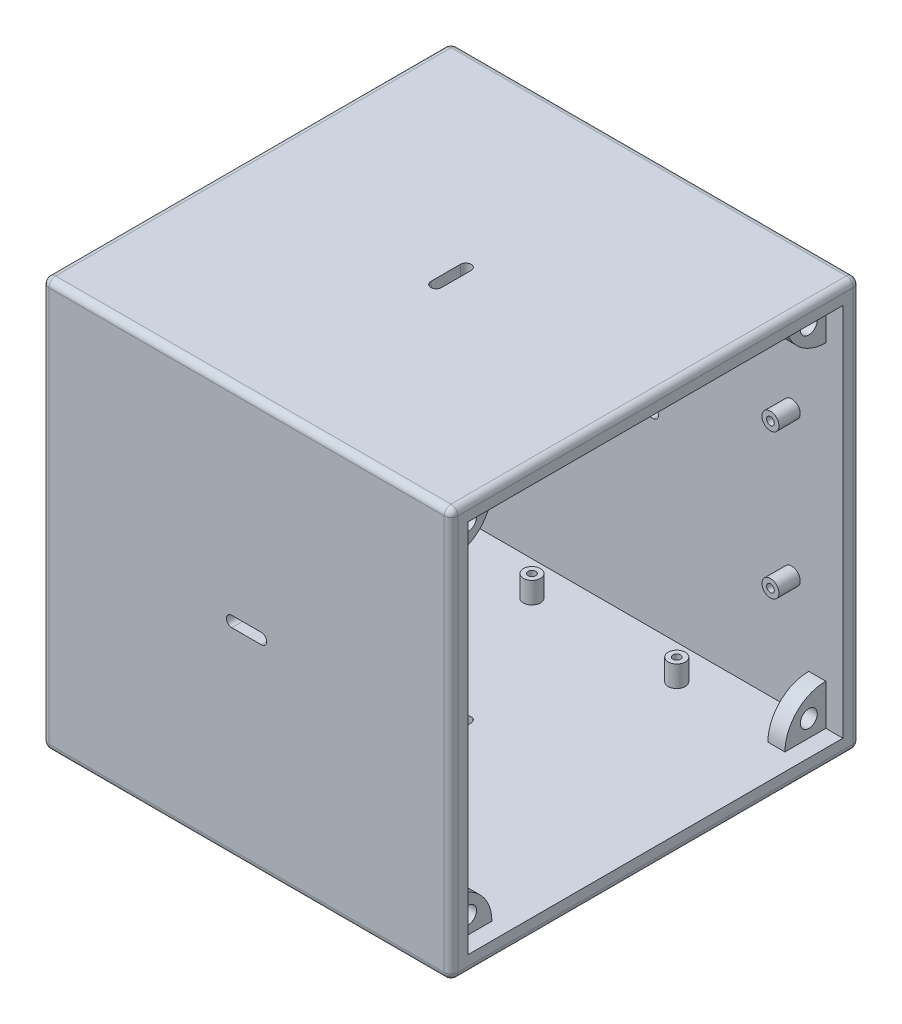
SolidWorks part; units mm, degrees
ref_plane "Front Plane" through (0, 0, 0) normal (0, 0, 1) x (1, 0, 0)
ref_plane "Top Plane" through (0, 0, 0) normal (0, 1, 0) x (1, 0, 0)
ref_plane "Right Plane" through (0, 0, 0) normal (1, 0, 0) x (0, 0, -1)
sketch "Sketch1" plane through (0, 0, 0) normal (0, 1, 0) x (1, 0, 0)
  line L1 (-76.2, -76.2) -> (76.2, -76.2)
  line L2 (-76.2, -76.2) -> (-76.2, 76.2)
  line L3 (-76.2, 76.2) -> (76.2, 76.2)
  line L4 (76.2, -76.2) -> (76.2, 76.2)
  line L5 (-76.2, -76.2) -> (76.2, 76.2) construction
  line L6 (-76.2, 76.2) -> (76.2, -76.2) construction
  point P0 (0, 0)
  dimension "D1" = 152.4
  dimension "D2" = 152.4
extrude "Boss-Extrude1" add sketch "Sketch1" along normal blind 152.4
shell "Shell2" thickness 6.35
ref_plane "Symmetry Top Plane" through (0, 76.2, 0) normal (0, 1, 0) x (1, 0, 0)
sketch "Sketch2" plane through (-69.85, 0, 0) normal (1, 0, 0) x (0, 0, -1)
  line L0 (-5.5, 76.2) -> (5.5, 76.2) construction
  line L1 (-7.5, 74.2) -> (7.5, 74.2) construction
  line L2 (-7.5, 74.2) -> (-7.5, 78.2) construction
  line L3 (-7.5, 78.2) -> (7.5, 78.2) construction
  line L4 (7.5, 74.2) -> (7.5, 78.2) construction
  line L5 (-7.5, 74.2) -> (7.5, 78.2)
  line L6 (-7.5, 78.2) -> (7.5, 74.2)
  line L7 (-5.5, 78.2) -> (5.5, 78.2)
  line L8 (-5.5, 74.2) -> (5.5, 74.2)
  line L10 (19, 73.2) -> (31, 73.2)
  line L11 (19, 73.2) -> (19, 79.2)
  line L12 (19, 79.2) -> (31, 79.2)
  line L13 (31, 73.2) -> (31, 79.2)
  line L14 (19, 73.2) -> (31, 79.2) construction
  line L15 (19, 79.2) -> (31, 73.2) construction
  line L16 (-31, 73.2) -> (-19, 73.2)
  line L17 (-31, 73.2) -> (-31, 79.2)
  line L18 (-31, 79.2) -> (-19, 79.2)
  line L19 (-19, 73.2) -> (-19, 79.2)
  line L20 (-31, 73.2) -> (-19, 79.2) construction
  line L21 (-31, 79.2) -> (-19, 73.2) construction
  arc A0 (-5.5, 78.2) -> (-5.5, 74.2) centre (-5.5, 76.2) ccw
  arc A1 (5.5, 74.2) -> (5.5, 78.2) centre (5.5, 76.2) ccw
  point P0 (0, 76.2)
  point P8 (0, 76.2)
  point P13 (-7.5, 76.2)
  point P14 (7.5, 76.2)
  point P15 (25, 76.2)
  point P20 (-25, 76.2)
  dimension "D6" = 2
  dimension "D1" = 15
  dimension "D2" = 4
  dimension "D3" = 76.2
  dimension "D4" = 0
  dimension "D5" = 25
  dimension "D7" = 15
  dimension "D8" = 12
  dimension "D9" = 6
  dimension "D10" = 25
  dimension "D11" = 25
  dimension "D12" = 6
  dimension "D13" = 12
  dimension "D14" = 25
extrude "Cut-Extrude3" cut sketch "Sketch2" along direction (1, 0, 0) on the side against the normal blind 6.35 contours L8 A1 L6 L5 A0 | L6 A1 L5 | L5 A1 L7 A0 L6 | L6 A0 L5
sketch "Sketch3" plane through (0, 0, -69.85) normal (0, 0, 1) x (1, 0, 0)
  line L0 (-5.5, 76.2) -> (5.5, 76.2) construction
  line L1 (-7.5, 74.2) -> (7.5, 74.2) construction
  line L2 (-7.5, 74.2) -> (-7.5, 78.2) construction
  line L3 (-7.5, 78.2) -> (7.5, 78.2) construction
  line L4 (7.5, 74.2) -> (7.5, 78.2) construction
  line L5 (-7.5, 74.2) -> (7.5, 78.2)
  line L6 (-7.5, 78.2) -> (7.5, 74.2)
  line L7 (-5.5, 78.2) -> (5.5, 78.2)
  line L8 (-5.5, 74.2) -> (5.5, 74.2)
  arc A0 (-5.5, 78.2) -> (-5.5, 74.2) centre (-5.5, 76.2) ccw
  arc A1 (5.5, 74.2) -> (5.5, 78.2) centre (5.5, 76.2) ccw
  point P0 (0, 76.2)
  point P7 (0, 76.2)
  point P12 (-7.5, 76.2)
  point P13 (7.5, 76.2)
  dimension "D3" = 2
  dimension "D6" = 76.2
  dimension "D1" = 15
  dimension "D2" = 4
  dimension "D4" = 15
  dimension "D5" = 0
extrude "Cut-Extrude4" cut sketch "Sketch3" against normal blind 6.35 contours L8 A1 L7 A0
sketch "Sketch4" plane through (0, 0, 69.85) normal (0, 0, -1) x (-1, 0, 0)
  line L0 (-5.5, 76.2) -> (5.5, 76.2) construction
  line L1 (-7.5, 74.2) -> (7.5, 74.2) construction
  line L2 (-7.5, 74.2) -> (-7.5, 78.2) construction
  line L3 (-7.5, 78.2) -> (7.5, 78.2) construction
  line L4 (7.5, 74.2) -> (7.5, 78.2) construction
  line L5 (-7.5, 74.2) -> (7.5, 78.2)
  line L6 (-7.5, 78.2) -> (7.5, 74.2)
  line L7 (-5.5, 78.2) -> (5.5, 78.2)
  line L8 (-5.5, 74.2) -> (5.5, 74.2)
  arc A0 (-5.5, 78.2) -> (-5.5, 74.2) centre (-5.5, 76.2) ccw
  arc A1 (5.5, 74.2) -> (5.5, 78.2) centre (5.5, 76.2) ccw
  point P0 (0, 76.2)
  point P7 (0, 76.2)
  point P12 (-7.5, 76.2)
  point P13 (7.5, 76.2)
  dimension "D3" = 2
  dimension "D1" = 15
  dimension "D2" = 4
  dimension "D4" = 15
  dimension "D5" = 0
  dimension "D6" = 76.2
extrude "Cut-Extrude5" cut sketch "Sketch4" against normal blind 6.35 contours L7 A1 L8 A0
sketch "Sketch5" plane through (0, 146.05, 0) normal (0, -1, 0) x (1, 0, 0)
  line L0 (0, -5.5) -> (0, 5.5) construction
  line L1 (-2, -5.5) -> (-2, 5.5)
  line L2 (2, -5.5) -> (2, 5.5)
  arc A0 (-2, -5.5) -> (2, -5.5) centre (0, -5.5) ccw
  arc A1 (2, 5.5) -> (-2, 5.5) centre (0, 5.5) ccw
  point P2 (0, 0)
  point P8 (0, -7.5)
  point P9 (0, 7.5)
  dimension "D1" = 15
  dimension "D2" = 4
extrude "Cut-Extrude6" cut sketch "Sketch5" against normal blind 6.35
mirror "Mirror1" about plane through (0, 76.2, 0) normal (0, 1, 0) of "Cut-Extrude6"
sketch "Sketch6" plane through (0, 146.05, 0) normal (0, -1, 0) x (1, 0, 0)
  line L0 (76.2, -76.2) -> (69.85, -76.2) construction
  line L1 (76.2, -76.2) -> (-76.2, -76.2) construction
  line L3 (69.85, -76.2) -> (63.5, -76.2)
  line L4 (69.85, -76.2) -> (69.85, 76.2)
  line L5 (69.85, 76.2) -> (63.5, 76.2)
  line L6 (63.5, -76.2) -> (63.5, 76.2)
  dimension "D1" = 6.35
  dimension "D2" = 152.4
  dimension "D3" = 6.35
extrude "Boss-Extrude2" add sketch "Sketch6" along normal blind 139.7
sketch "Sketch7" plane through (69.85, 0, 0) normal (1, 0, 0) x (0, 0, -1)
  line L0 (-69.85, 146.05) -> (69.85, 146.05) construction
  line L1 (69.85, 146.05) -> (69.85, 6.35) construction
  line L2 (-69.85, 6.35) -> (-69.85, 146.05) construction
  line L3 (69.85, 146.05) -> (69.85, 6.35) construction
  line L4 (69.85, 6.35) -> (-69.85, 6.35) construction
  line L5 (69.85, 21.59) -> (69.85, 130.81)
  line L6 (54.61, 146.05) -> (-54.61, 146.05)
  line L7 (-69.85, 21.59) -> (-69.85, 130.81)
  line L8 (54.61, 6.35) -> (-54.61, 6.35)
  arc A0 (54.61, 146.05) -> (69.85, 130.81) centre (69.85, 146.05) ccw
  arc A1 (-54.61, 146.05) -> (-69.85, 130.81) centre (-69.85, 146.05) cw
  arc A2 (69.85, 21.59) -> (54.61, 6.35) centre (69.85, 6.35) ccw
  arc A3 (-69.85, 21.59) -> (-54.61, 6.35) centre (-69.85, 6.35) cw
  dimension "D1" = 15.24
  dimension "D2" = 15.24
  dimension "D3" = 15.24
  dimension "D4" = 15.24
extrude "Cut-Extrude7" cut sketch "Sketch7" against normal blind 6.35
sketch "Sketch8" plane through (69.85, 0, 0) normal (1, 0, 0) x (0, 0, -1)
  line L1 (76.835, 76.2) -> (-76.835, 76.2) construction
  line L2 (0, 83.82) -> (0, -83.82) construction
  circle A0 centre (63.5, 12.7) radius 3.175
  circle A1 centre (63.5, 139.7) radius 3.175
  circle A2 centre (-63.5, 139.7) radius 3.175
  circle A3 centre (-63.5, 12.7) radius 3.175
  point P5 (63.4563, 12.9858)
  dimension "D1" = 6.35
  dimension "D2" = 6.35
  dimension "D3" = 6.35
extrude "Cut-Extrude8" cut sketch "Sketch8" against normal blind 6.35
sketch "Sketch10" plane through (0, 0, 69.85) normal (0, 0, -1) x (-1, 0, 0)
  circle A1 centre (-57.15, 49.2125) radius 1.4288
  circle A2 centre (57.15, 49.2125) radius 1.4288
  circle A3 centre (-57.15, 103.1875) radius 1.4288
  circle A6 centre (57.15, 103.1875) radius 1.4287
  circle A7 centre (-57.15, 103.1875) radius 3.175
  circle A8 centre (-57.15, 49.2125) radius 3.175
  circle A9 centre (57.15, 49.2125) radius 3.175
  circle A10 centre (57.15, 103.1875) radius 3.175
  dimension "D1" = 114.3
  dimension "D3" = 2.8575
  dimension "D4" = 2.8575
  dimension "D5" = 2.8575
  dimension "D6" = 2.8575
  dimension "D13" = 6.35
  dimension "D14" = 6.35
  dimension "D15" = 6.35
  dimension "D16" = 6.35
  dimension "D2" = 53.975
  dimension "D7" = 114.3
  dimension "D8" = 53.975
  dimension "D9" = 57.15
  dimension "D10" = 49.2125
  dimension "D11" = 57.15
  dimension "D12" = 57.15
extrude "Boss-Extrude3" add sketch "Sketch10" along normal blind 7.9375
mirror "Mirror2" about plane through (0, 0, 0) normal (0, 0, 1) of "Boss-Extrude3"
sketch "Sketch11" plane through (0, 6.35, 0) normal (0, 1, 0) x (1, 0, 0)
  circle A0 centre (26.9875, -57.15) radius 1.4288
  circle A1 centre (26.9875, 57.15) radius 1.4288
  circle A2 centre (-26.9875, -57.15) radius 1.4288
  circle A3 centre (-26.9875, 57.15) radius 1.4287
  circle A4 centre (-26.9875, -57.15) radius 3.175
  circle A5 centre (26.9875, -57.15) radius 3.175
  circle A6 centre (26.9875, 57.15) radius 3.175
  circle A7 centre (-26.9875, 57.15) radius 3.175
  dimension "D3" = 2.8575
  dimension "D4" = 2.8575
  dimension "D5" = 2.8575
  dimension "D6" = 2.8575
  dimension "D9" = 6.35
  dimension "D10" = 6.35
  dimension "D11" = 6.35
  dimension "D12" = 6.35
  dimension "D1" = 114.3
  dimension "D2" = 53.975
  dimension "D7" = 114.3
  dimension "D8" = 53.975
  dimension "D13" = 57.15
  dimension "D14" = 26.9875
  dimension "D15" = 26.9875
  dimension "D16" = 26.9875
extrude "Boss-Extrude4" add sketch "Sketch11" along normal blind 7.9375
mirror "Mirror3" about plane through (0, 76.2, 0) normal (0, 1, 0) of "Boss-Extrude4"
sketch "Sketch15" plane through (-69.85, 0, 0) normal (1, 0, 0) x (0, 0, -1)
  circle A0 centre (-57.15, 49.2125) radius 1.4288
  circle A1 centre (57.15, 49.2125) radius 1.4288
  circle A2 centre (-57.15, 103.1875) radius 1.4288
  circle A3 centre (57.15, 103.1875) radius 1.4287
  circle A4 centre (-57.15, 103.1875) radius 3.175
  circle A5 centre (-57.15, 49.2125) radius 3.175
  circle A6 centre (57.15, 49.2125) radius 3.175
  circle A7 centre (57.15, 103.1875) radius 3.175
  point P14 (-41.366, 94.4094)
  dimension "D3" = 2.8575
  dimension "D4" = 2.8575
  dimension "D5" = 2.8575
  dimension "D6" = 2.8575
  dimension "D9" = 6.35
  dimension "D10" = 6.35
  dimension "D11" = 6.35
  dimension "D12" = 6.35
  dimension "D1" = 114.3
  dimension "D2" = 53.975
  dimension "D7" = 114.3
  dimension "D8" = 53.975
  dimension "D13" = 57.15
  dimension "D14" = 49.2125
  dimension "D15" = 49.2125
  dimension "D16" = 49.2125
extrude "Boss-Extrude5" add sketch "Sketch15" along normal blind 7.9375
fillet "Fillet1" radius 2.54 4 edges at (76.2, 76.2, 76.2) (-76.2, 76.2, 76.2) (-76.2, 76.2, -76.2) (76.2, 76.2, -76.2)
fillet "Fillet2" radius 2.54 16 edges at (-75.4561, 152.4, 75.4561) (-76.2, 152.4, 0) (-75.4561, 152.4, -75.4561) (75.4561, 152.4, -75.4561) (76.2, 152.4, 0) (75.4561, 152.4, 75.4561) (-75.4561, 0, 75.4561) (-76.2, 0, 0) (-75.4561, 0, -75.4561) (75.4561, 0, -75.4561) (76.2, 0, 0) (75.4561, 0, 75.4561) (0, 0, -76.2) (0, 152.4, -76.2) (0, 152.4, 76.2) (0, 0, 76.2)
